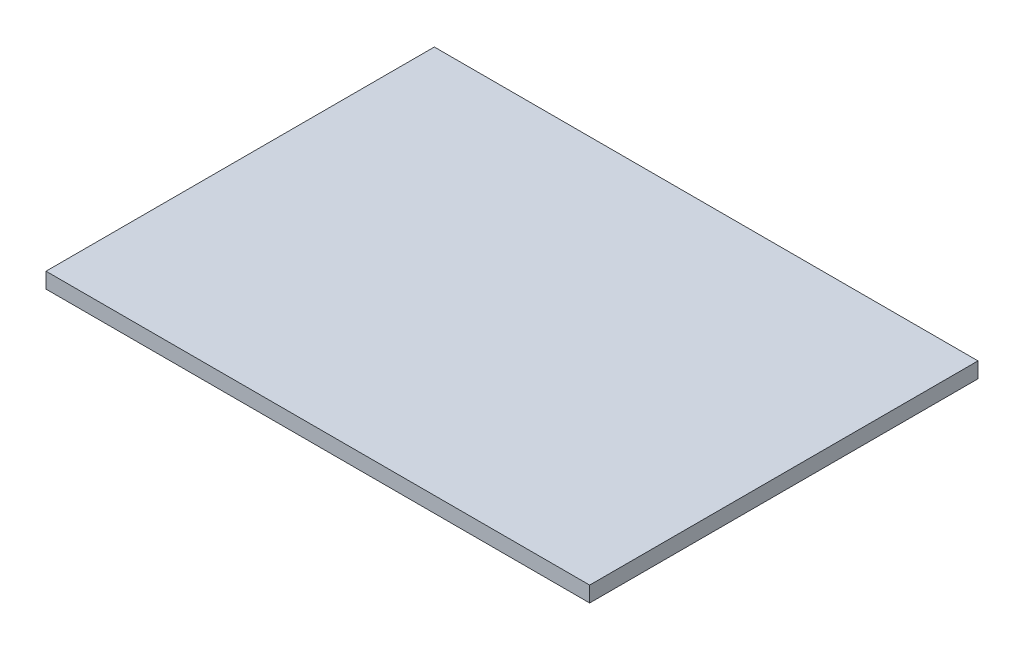
SolidWorks part; units mm, degrees
ref_plane "Front Plane" through (0, 0, 0) normal (0, 0, 1) x (1, 0, 0)
ref_plane "Top Plane" through (0, 0, 0) normal (0, 1, 0) x (1, 0, 0)
ref_plane "Right Plane" through (0, 0, 0) normal (1, 0, 0) x (0, 0, -1)
sketch "Sketch1" plane through (0, 0, 0) normal (0, 1, 0) x (1, 0, 0)
  line L1 (0, 0) -> (70, 0)
  line L2 (0, 0) -> (0, 50)
  line L3 (0, 50) -> (70, 50)
  line L4 (70, 0) -> (70, 50)
  dimension "D1" = 50
  dimension "D2" = 70
extrude "Boss-Extrude1" add sketch "Sketch1" along normal blind 2
